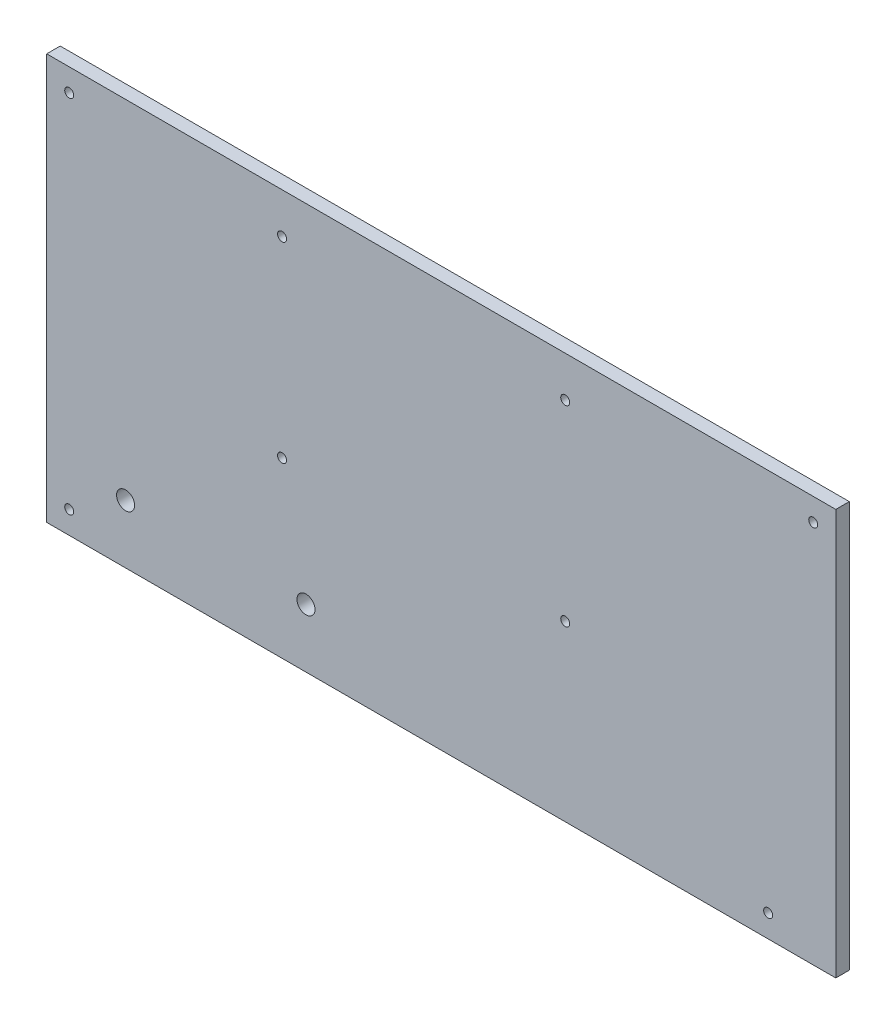
SolidWorks part; units mm, degrees
material "Faia"
ref_plane "Plano frontal" through (0, 0, 0) normal (0, 0, 1) x (1, 0, 0)
ref_plane "Plano superior" through (0, 0, 0) normal (0, 1, 0) x (1, 0, 0)
ref_plane "Plano direito" through (0, 0, 0) normal (1, 0, 0) x (0, 0, -1)
sketch "Esboço1" plane through (0, 0, 0) normal (0, 0, 1) x (1, 0, 0)
  line L0 (175, 0) -> (-175, 0) construction
  line L1 (-175, 90) -> (175, 90)
  line L2 (-175, 90) -> (-175, -90)
  line L3 (-175, -90) -> (175, -90)
  line L4 (175, 90) -> (175, -90)
  line L5 (-175, 90) -> (175, -90) construction
  line L6 (-175, -90) -> (175, 90) construction
  line L7 (165, 80) -> (165, 90) construction
  line L8 (145, -80) -> (145, -90) construction
  line L9 (-140, -64) -> (-60, -64) construction
  circle A0 centre (145, -80) radius 2
  circle A1 centre (165, 80) radius 2
  circle A2 centre (-165, 80) radius 2
  circle A3 centre (-165, -80) radius 2
  circle A4 centre (-140, -64) radius 4
  circle A5 centre (-60, -64) radius 4
  point P0 (0, 0)
  point P21 (5, 0)
  point P23 (-100, -64)
  dimension "D5" = 30
  dimension "D8" = 80
  dimension "D10" = 75
  dimension "D3" = 4
  dimension "D11" = 8
  dimension "D1" = 350
  dimension "D2" = 180
  dimension "D4" = 10
  dimension "D7" = 10
  dimension "D9" = 26
  dimension "D6" = 10
extrude "Ressalto-extrusão1" add sketch "Esboço1" along normal blind 6
sketch "Esboço2" plane through (0, 0, 6) normal (0, 0, 1) x (1, 0, 0)
  line L0 (-175, 90) -> (175, 90) construction
  line L1 (175, 90) -> (175, -90) construction
  circle A0 centre (55, 72) radius 2
  circle A1 centre (-70.6, 72) radius 2
  circle A2 centre (-70.6, -13) radius 2
  circle A3 centre (55, -13) radius 2
  dimension "D2" = 4
  dimension "D1" = 125.6
  dimension "D3" = 85
  dimension "D4" = 18
  dimension "D5" = 120
extrude "Corte-extrusão1" cut sketch "Esboço2" against normal blind 10
